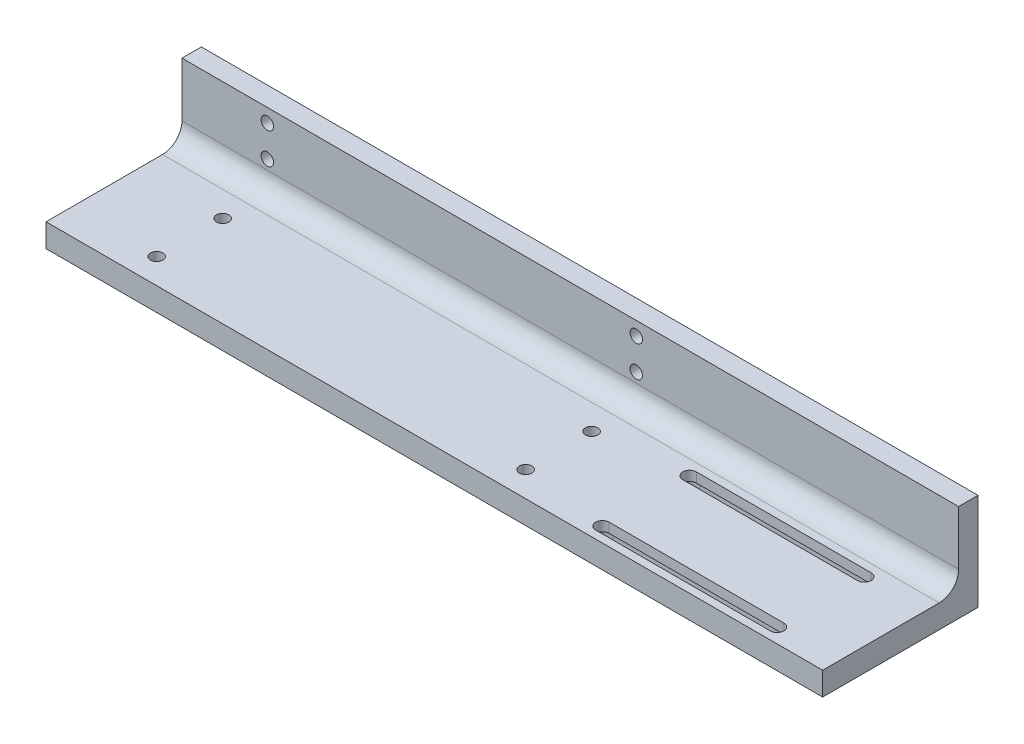
SolidWorks part; units mm, degrees
material "ABS"
ref_plane "Front Plane" through (0, 0, 0) normal (0, 0, 1) x (1, 0, 0)
ref_plane "Top Plane" through (0, 0, 0) normal (0, 1, 0) x (1, 0, 0)
ref_plane "Right Plane" through (0, 0, 0) normal (1, 0, 0) x (0, 0, -1)
sketch "Sketch6" plane through (0, 0, 0) normal (1, 0, 0) x (0, 0, -1)
  line L0 (0, 2.5) -> (30, 2.5)
  line L1 (35, 7.5) -> (35, 21.5)
  line L2 (35, 21.5) -> (40, 21.5)
  line L3 (0, 2.5) -> (0, -3.5)
  line L4 (0, -3.5) -> (40, -3.5)
  line L5 (40, -3.5) -> (40, 21.5)
  arc A0 (30, 2.5) -> (35, 7.5) centre (30, 7.5) ccw
  dimension "D1" = 5
extrude "Boss-Extrude8" add sketch "Sketch6" along normal blind 200
sketch "Sketch4" plane through (0, 0, 0) normal (0, 1, 0) x (1, 0, 0)
  line L0 (139.5, 26.225) -> (184.5, 26.225) construction
  line L5 (139.5, 27.975) -> (184.5, 27.975)
  line L6 (139.5, 24.475) -> (184.5, 24.475)
  line L7 (139.5, 3.775) -> (184.5, 3.775) construction
  line L8 (139.5, 5.525) -> (184.5, 5.525)
  line L9 (139.5, 2.025) -> (184.5, 2.025)
  circle A0 centre (22, 23.5) radius 1.6
  circle A1 centre (22, 6.5) radius 1.6
  circle A2 centre (117, 23.5) radius 1.6
  circle A3 centre (117, 6.5) radius 1.6
  arc A4 (139.5, 27.975) -> (139.5, 24.475) centre (139.5, 26.225) ccw
  arc A5 (184.5, 24.475) -> (184.5, 27.975) centre (184.5, 26.225) ccw
  arc A6 (139.5, 5.525) -> (139.5, 2.025) centre (139.5, 3.775) ccw
  arc A7 (184.5, 2.025) -> (184.5, 5.525) centre (184.5, 3.775) ccw
  point P18 (162, 26.225)
  point P29 (162, 3.775)
sketch "Sketch5" plane through (0, 0, 0) normal (0, 1, 0) x (1, 0, 0)
  line L0 (184.5, 26.225) -> (139.5, 26.225) construction
  line L1 (1, 30) -> (201, 30) construction
  line L2 (1, 30) -> (1, 0) construction
  line L3 (1, 0) -> (201, 0) construction
  line L4 (201, 30) -> (201, 0) construction
  line L37 (184.5, 23.475) -> (139.5, 23.475)
  line L38 (184.5, 28.975) -> (139.5, 28.975)
  line L39 (184.5, 3.775) -> (139.5, 3.775) construction
  line L40 (184.5, 1.025) -> (139.5, 1.025)
  line L41 (184.5, 6.525) -> (139.5, 6.525)
  arc A0 (184.5, 23.475) -> (184.5, 28.975) centre (184.5, 26.225) ccw
  arc A1 (139.5, 28.975) -> (139.5, 23.475) centre (139.5, 26.225) ccw
  arc A2 (184.5, 1.025) -> (184.5, 6.525) centre (184.5, 3.775) ccw
  arc A3 (139.5, 6.525) -> (139.5, 1.025) centre (139.5, 3.775) ccw
  circle A4 centre (22, 23.5) radius 1.6
  circle A5 centre (22, 6.5) radius 1.6
  circle A6 centre (117, 23.5) radius 1.6
  circle A7 centre (117, 6.5) radius 1.6
  point P58 (162, 26.225)
  point P63 (162, 3.775)
sketch "Sketch7" plane through (0, 0, -35) normal (0, 0, 1) x (1, 0, 0)
  circle A0 centre (22, 10) radius 1.6
  circle A1 centre (22, 18) radius 1.6
  circle A2 centre (117, 10) radius 1.6
  circle A3 centre (117, 18) radius 1.6
extrude "Cut-Extrude1" cut sketch "Sketch4" along normal up to surface (2.5 mm away) up to face at (100, 2.5, -15)
extrude "Cut-Extrude2" cut sketch "Sketch5" against normal up to surface (3.5 mm away) up to face at (100, -3.5, -20)
extrude "Cut-Extrude3" cut sketch "Sketch7" against normal up to surface (5 mm away) up to face at (100, 9, -40)
